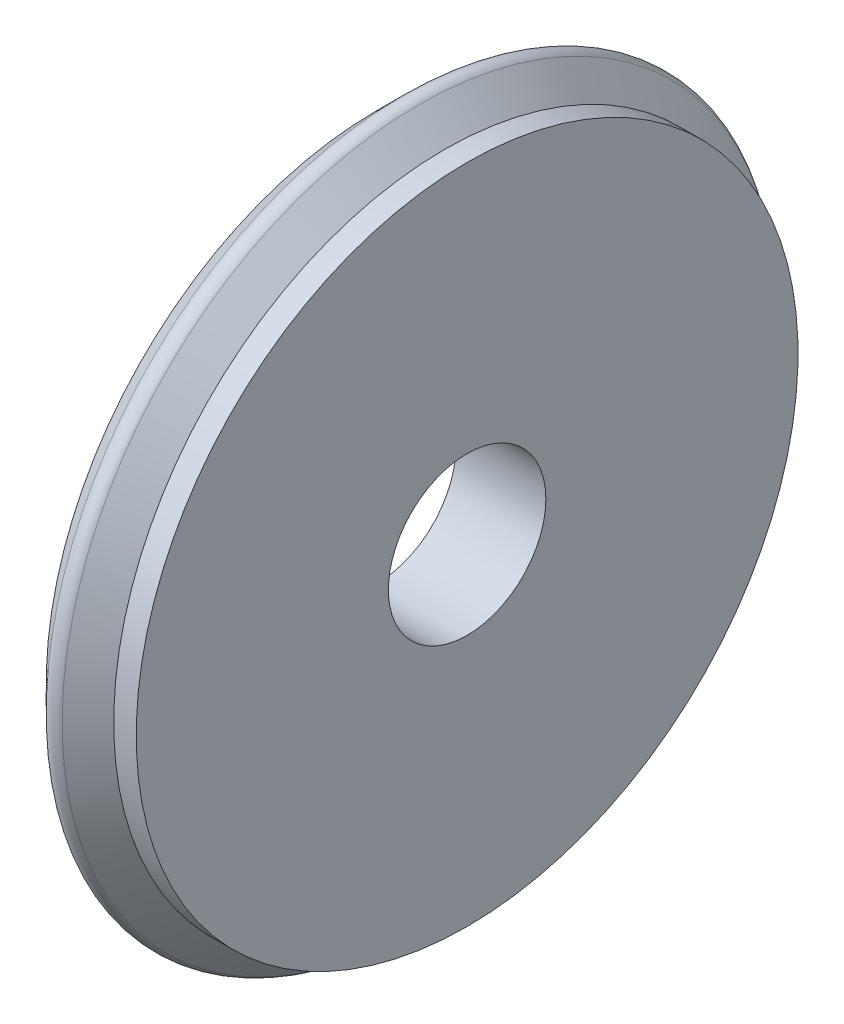
SolidWorks part; units mm, degrees
material "Alliage 1060"
ref_plane "Face" through (0, 0, 0) normal (0, 0, 1) x (1, 0, 0)
ref_plane "Dessus" through (0, 0, 0) normal (0, 1, 0) x (1, 0, 0)
ref_plane "Droite" through (0, 0, 0) normal (1, 0, 0) x (0, 0, -1)
sketch "Esquisse1" plane through (0, 0, 0) normal (0, 0, 1) x (1, 0, 0)
  line L0 (0, 0) -> (0, 14.7071)
  line L1 (0, 14.7071) -> (1.1464, 15.8536)
  line L3 (4, 0) -> (0, 0)
  line L4 (1.5, 15.5) -> (1.5, 16) construction
  line L6 (0, 0) -> (4, 0) construction
  line L7 (3, 14.7071) -> (4, 14.7071)
  line L8 (1.8536, 15.8536) -> (3, 14.7071)
  line L9 (1.5, 15.5) -> (1.5, 14.7071) construction
  line L15 (3, 14.7071) -> (0, 14.7071) construction
  line L16 (4, 14.7071) -> (4, 0)
  arc A0 (1.1464, 15.8536) -> (1.8536, 15.8536) centre (1.5, 15.5) cw
  dimension "D5" = 90
  dimension "D3" = 0.5
  dimension "D2" = 3
  dimension "D4" = 16
  dimension "D11" = 4
revolve "Révolution1" add sketch "Esquisse1" angle 360 about L6
sketch "Esquisse6" plane through (0, 0, 0) normal (0, 0, 1) x (1, 0, 0)
  line L0 (0, 0) -> (0, 3.5)
  line L2 (0, 3.5) -> (4, 3.5)
  line L3 (4, -14.7071) -> (4, 14.7071) construction
  line L8 (4, 3.5) -> (4, 0)
  line L9 (4, 0) -> (0, 0) construction
  line L10 (0, 0) -> (4, 0)
  dimension "D1" = 7
revolve "Enlèvement de matière-Révolution1" cut sketch "Esquisse6" angle 360 about L9
